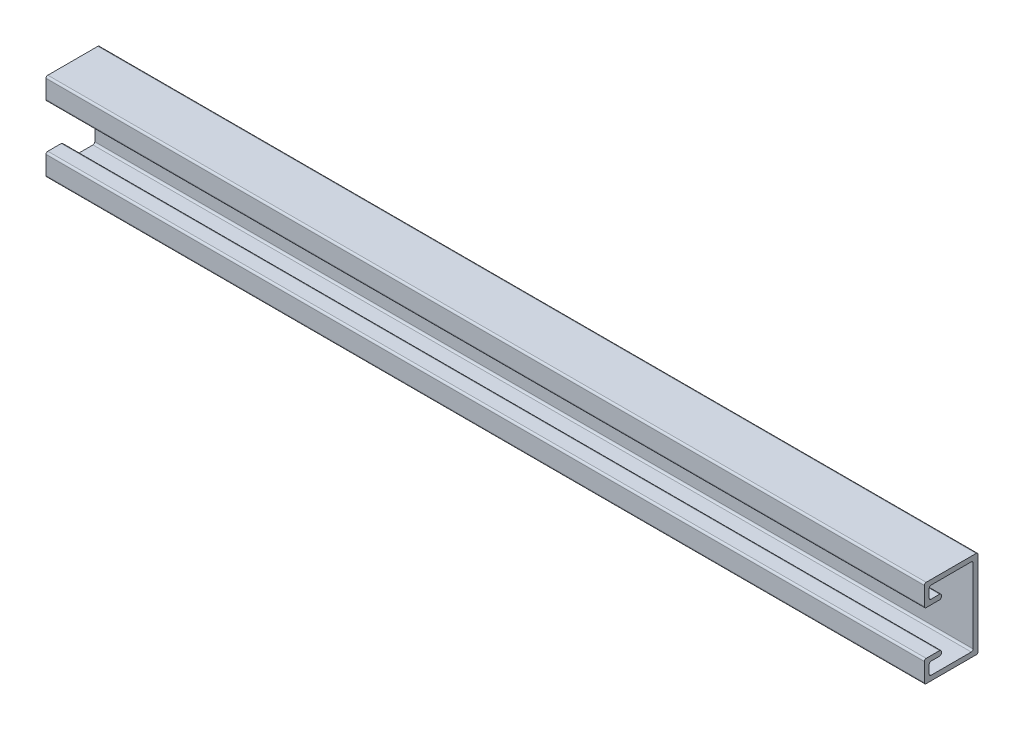
SolidWorks part; units mm, degrees
material "1060-O (SS)"
ref_plane "Front Plane" through (0, 0, 0) normal (0, 0, 1) x (1, 0, 0)
ref_plane "Top Plane" through (0, 0, 0) normal (0, 1, 0) x (1, 0, 0)
ref_plane "Right Plane" through (0, 0, 0) normal (1, 0, 0) x (0, 0, -1)
sketch "Sketch1" plane through (0, 0, 0) normal (1, 0, 0) x (0, 0, -1)
  line L0 (0, 0) -> (0, 81.28)
  line L7 (-45.72, 12.7) -> (-33.02, 12.7)
  line L8 (-45.72, 0) -> (-45.72, 12.7)
  line L9 (0, 0) -> (-45.72, 0)
  line L10 (-45.72, 68.58) -> (-33.02, 68.58)
  line L11 (-45.72, 81.28) -> (-45.72, 68.58)
  line L12 (0, 81.28) -> (-45.72, 81.28)
  dimension "D1" = 45.72
  dimension "D2" = 81.28
  dimension "D3" = 12.7
  dimension "D4" = 12.7
extrude "Extrude-Thin1" add sketch "Sketch1" along normal blind 914.4 thin
fillet "Fillet1" radius 1.905 16 edges at (457.2, 12.7, 45.72) (457.2, 63.5, 50.8) (457.2, -5.08, 50.8) (457.2, 0, 0) (457.2, -5.08, -5.08) (457.2, 86.36, 50.8) (457.2, 86.36, -5.08) (457.2, 0, 45.72) (457.2, 17.78, 50.8) (457.2, 12.7, 33.02) (457.2, 17.78, 33.02) (457.2, 63.5, 33.02) (457.2, 68.58, 33.02) (457.2, 68.58, 45.72) (457.2, 81.28, 45.72) (457.2, 81.28, 0)
